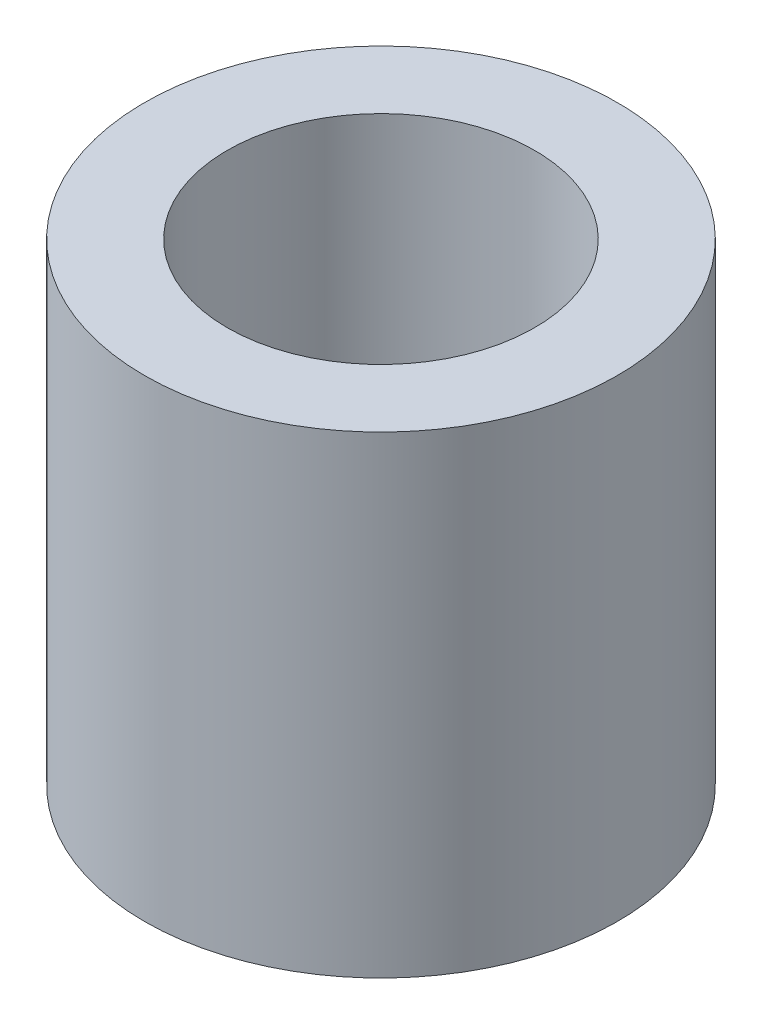
SolidWorks part; units mm, degrees
material "ABS"
ref_plane "前视基准面" through (0, 0, 0) normal (0, 0, 1) x (1, 0, 0)
ref_plane "上视基准面" through (0, 0, 0) normal (0, 1, 0) x (1, 0, 0)
ref_plane "右视基准面" through (0, 0, 0) normal (1, 0, 0) x (0, 0, -1)
other "Configuration Table"
sketch "草图1" plane through (0, 0, 0) normal (0, 1, 0) x (1, 0, 0)
  line L1 (2.8868, 0) -> (1.4434, 2.5) construction
  line L2 (1.4434, 2.5) -> (-1.4434, 2.5) construction
  line L3 (-1.4434, 2.5) -> (-2.8868, 0) construction
  line L4 (-2.8868, 0) -> (-1.4434, -2.5) construction
  line L5 (-1.4434, -2.5) -> (1.4434, -2.5) construction
  line L6 (1.4434, -2.5) -> (2.8868, 0) construction
  circle A0 centre (0, 0) radius 3.25
  circle A1 centre (0, 0) radius 2.5 construction
  circle A2 centre (0, 0) radius 5
  dimension "D1" = 5
  dimension "D2" = 6.5
  dimension "D3" = 10
extrude "凸台-拉伸1" add sketch "草图1" along normal blind 10
